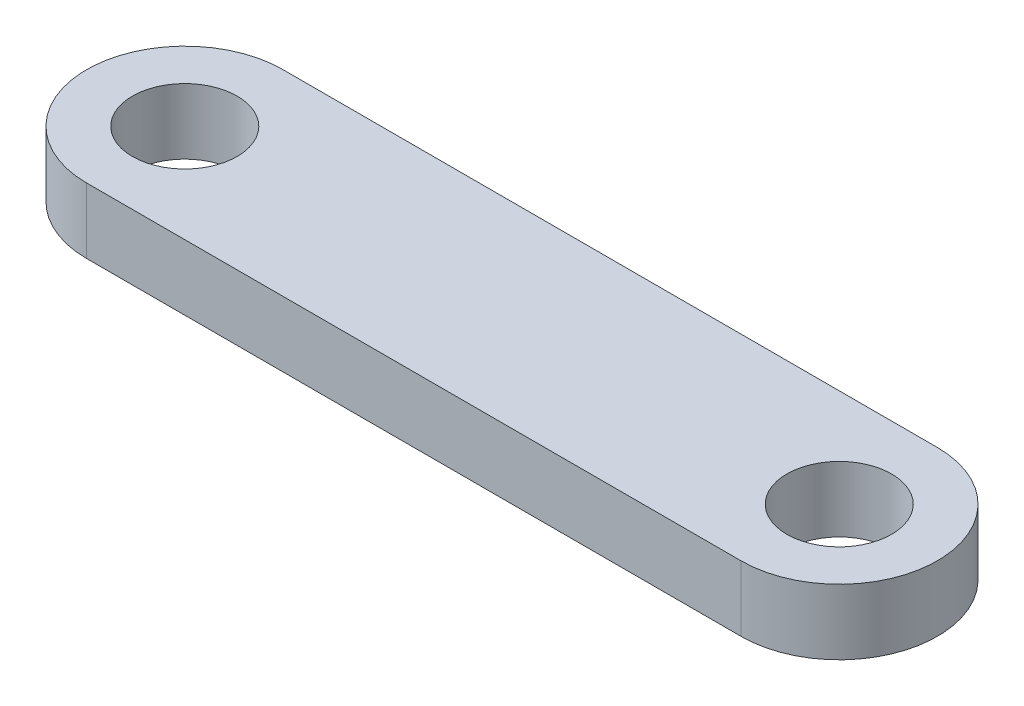
SolidWorks part; units mm, degrees
ref_plane "Front Plane" through (0, 0, 0) normal (0, 0, 1) x (1, 0, 0)
ref_plane "Top Plane" through (0, 0, 0) normal (0, 1, 0) x (1, 0, 0)
ref_plane "Right Plane" through (0, 0, 0) normal (1, 0, 0) x (0, 0, -1)
sketch "Sketch1" plane through (0, 0, 0) normal (0, 1, 0) x (1, 0, 0)
  line L0 (-25, 0) -> (25, 0) construction
  line L1 (-25, 7.5) -> (25, 7.5)
  line L2 (-25, -7.5) -> (25, -7.5)
  arc A0 (-25, 7.5) -> (-25, -7.5) centre (-25, 0) ccw
  arc A1 (25, -7.5) -> (25, 7.5) centre (25, 0) ccw
  circle A2 centre (-25, 0) radius 4
  circle A3 centre (25, 0) radius 4
  point P3 (0, 0)
  dimension "D1" = 7.5
  dimension "D3" = 8
  dimension "D2" = 50
extrude "Boss-Extrude1" add sketch "Sketch1" along normal blind 5
